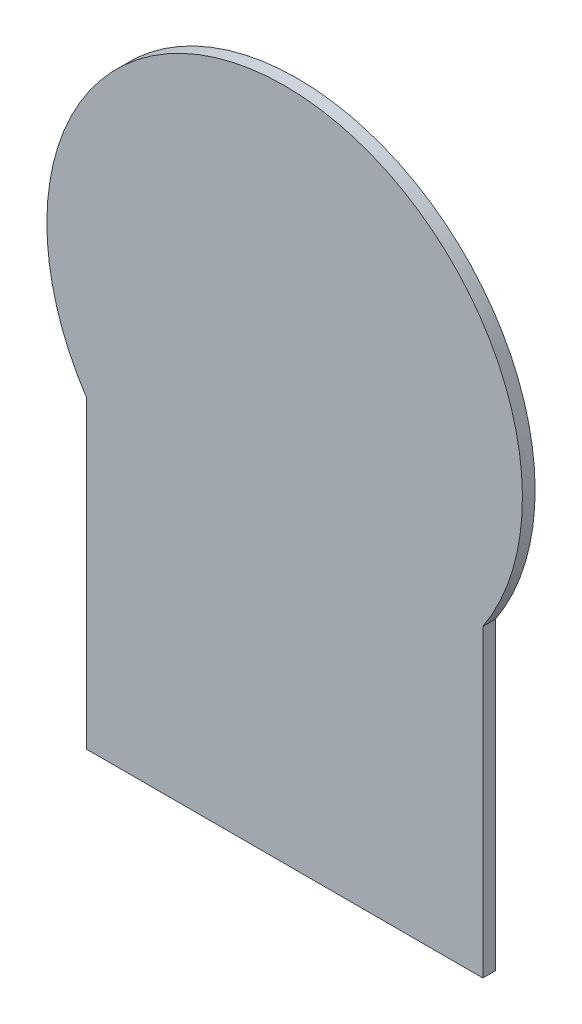
SolidWorks part; units mm, degrees
ref_plane "Front Plane" through (0, 0, 0) normal (0, 0, 1) x (1, 0, 0)
ref_plane "Top Plane" through (0, 0, 0) normal (0, 1, 0) x (1, 0, 0)
ref_plane "Right Plane" through (0, 0, 0) normal (1, 0, 0) x (0, 0, -1)
sketch "Sketch1" plane through (0, 0, 0) normal (0, 0, 1) x (1, 0, 0)
  line L2 (-3.175, -2.1061) -> (-3.175, -6.985)
  line L3 (-3.175, -6.985) -> (3.175, -6.985)
  line L4 (3.175, -2.1061) -> (3.175, -6.985)
  arc A0 (3.175, -2.1061) -> (-3.175, -2.1061) centre (0, 0) ccw
  dimension "D1" = 7.62
  dimension "D4" = 6.985
  dimension "D2" = 6.35
  dimension "D3" = 3.175
extrude "Boss-Extrude1" add sketch "Sketch1" along normal blind 0.2032
